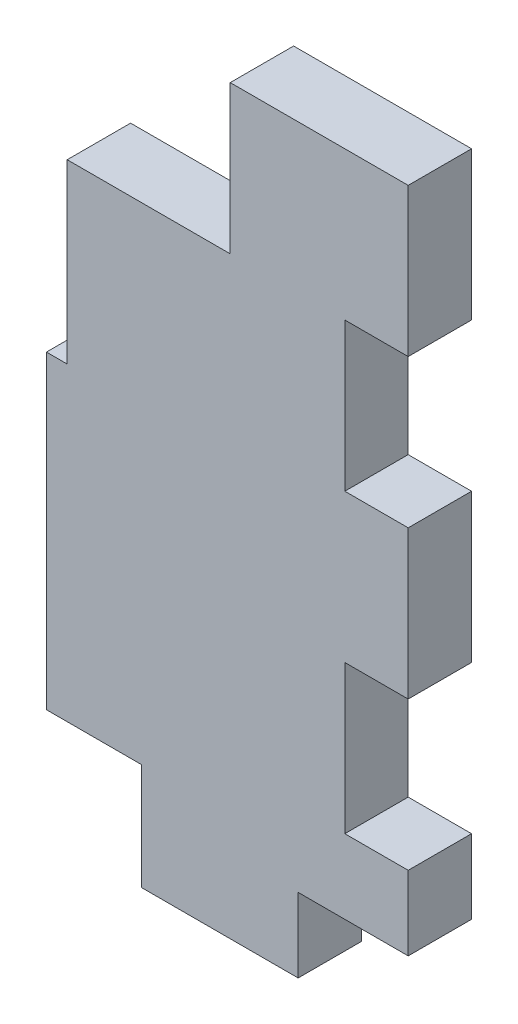
SolidWorks part; units mm, degrees
ref_plane "Front Plane" through (0, 0, 0) normal (0, 0, 1) x (1, 0, 0)
ref_plane "Top Plane" through (0, 0, 0) normal (0, 1, 0) x (1, 0, 0)
ref_plane "Right Plane" through (0, 0, 0) normal (1, 0, 0) x (0, 0, -1)
sketch "Sketch1" plane through (0, 0, 0) normal (0, 0, 1) x (1, 0, 0)
  line L0 (0, -0.475) -> (32.004, -0.475) construction
  line L4 (32.004, -26.67) -> (32.004, 26.67)
  line L5 (32.004, 26.67) -> (0, 26.67)
  line L6 (0, 26.67) -> (0, 12.9921)
  line L7 (0, 26.67) -> (0, -0.475) construction
  line L8 (8.2572, -26.67) -> (8.2572, -19.0119) construction
  line L9 (0, 26.67) -> (0, 12.9921) construction
  line L10 (32.004, 26.67) -> (27.4447, 26.67) construction
  line L11 (27.4447, 26.67) -> (27.4447, -26.67) construction
  line L12 (0, 12.9921) -> (27.4447, 12.9921) construction
  line L13 (0, 12.9921) -> (11.0096, 12.9921) construction
  line L19 (8.2572, -26.67) -> (32.004, -26.67) construction
  line L23 (8.2572, -19.0119) -> (12.8165, -19.0119) construction
  line L44 (32.004, 26.67) -> (27.4447, 26.67) construction
  line L45 (32.004, 26.67) -> (32.004, 16.002) construction
  line L46 (32.004, 16.002) -> (27.4447, 16.002) construction
  line L47 (27.4447, 26.67) -> (27.4447, 16.002) construction
  line L48 (27.4447, 16.002) -> (32.004, 16.002)
  line L49 (27.4447, 16.002) -> (27.4447, 5.334)
  line L50 (27.4447, 5.334) -> (32.004, 5.334)
  line L51 (32.004, 16.002) -> (32.004, 5.334)
  line L52 (27.4447, 5.334) -> (32.004, 5.334) construction
  line L53 (27.4447, 5.334) -> (27.4447, -5.334) construction
  line L54 (27.4447, -5.334) -> (32.004, -5.334) construction
  line L55 (32.004, 5.334) -> (32.004, -5.334) construction
  line L56 (27.4447, -5.334) -> (32.004, -5.334)
  line L57 (27.4447, -5.334) -> (27.4447, -16.002)
  line L58 (27.4447, -16.002) -> (32.004, -16.002)
  line L59 (32.004, -5.334) -> (32.004, -16.002)
  line L60 (27.4447, -16.002) -> (32.004, -16.002) construction
  line L61 (27.4447, -16.002) -> (27.4447, -26.67) construction
  line L62 (27.4447, -26.67) -> (32.004, -26.67) construction
  line L63 (32.004, -16.002) -> (32.004, -26.67) construction
  line L75 (6.4008, 21.336) -> (6.4008, 26.67) construction
  line L76 (6.4008, 21.336) -> (19.2024, 21.336) construction
  line L77 (6.4008, 21.336) -> (6.4008, 26.67) construction
  line L78 (6.4008, 26.67) -> (19.2024, 26.67)
  line L79 (19.2024, 21.336) -> (19.2024, 26.67)
  line L80 (19.2024, 21.336) -> (32.004, 21.336) construction
  line L81 (19.2024, 21.336) -> (19.2024, 26.67) construction
  line L82 (19.2024, 26.67) -> (32.004, 26.67) construction
  line L83 (32.004, 21.336) -> (32.004, 26.67) construction
  line L96 (12.8165, -19.0119) -> (12.8165, -26.67)
  line L97 (24.0884, -26.67) -> (24.0884, -21.336)
  line L98 (32.004, -21.336) -> (24.0884, -21.336)
  line L99 (0, 12.9921) -> (7.4752, 12.9921)
  line L100 (7.4752, 12.9921) -> (7.4752, 3.2715)
  line L101 (7.4752, 3.2715) -> (5.9802, 3.2715)
  line L103 (5.9802, -19.0119) -> (8.2572, -19.0119)
  line L104 (5.9802, -19.0119) -> (5.9802, 3.2715)
  line L105 (27.4447, 16.002) -> (0, 16.002) construction
  line L106 (19.2024, 21.336) -> (19.2024, 16.002)
  line L107 (19.2024, 16.002) -> (0, 16.002)
  line L108 (7.4752, 12.9921) -> (7.4752, 16.002)
  line L109 (7.4752, 16.002) -> (19.2024, 16.002)
  line L110 (12.8165, -19.0119) -> (8.2572, -19.0119)
  line L111 (12.8165, -26.67) -> (24.0884, -26.67)
  dimension "D2" = 53.34
  dimension "D6" = 4.5593
  dimension "D1" = 7.4752
  dimension "D3" = 9.7206
  dimension "D4" = 1.495
  dimension "D5" = 13.6779
  dimension "D7" = 4.5593
extrude "Boss-Extrude1" add sketch "Sketch1" along normal blind 4.5593
equation "\"D2@Sketch1\"=\"neck_height\""
equation "\"material_width\" = 0.1795"
equation "\"max32_width\" = 2.1"
equation "\"max32_length\" = 4.0"
equation "\"max32_hole_diameter\" = 0.12"
equation "\"max32_dist2hole_width\" = 0.1"
equation "\"max32_dist2hole1_length\" = 0.6"
equation "\"max32_dist2hole2_length\" = 3.8"
equation "\"head_height\" = 2.0"
equation "\"neck_height\" = \"max32_width\""
equation "\"washer_height\" = 0.1"
equation "\"wall_length\" = 3.5"
equation "\"wall_height\" = 1.5"
equation "\"extra_space\" = 0.25"
equation "\"arc_radius\" = \"wall_length\" + \"washer_height\" + \"neck_height\" + (\"head_height\"/2)"
equation "\"arc_wall_height\" = \"arc_radius\" + \"wall_length\" + \"extra_space\""
equation "\"foot_length\" = 1.0"
equation "\"peg_diameter\" = 0.2475"
equation "\"barring_diameter\" = 0.8657"
equation "\"imu_space\" = 0.8"
equation "\"encoder_height\" = 0.8587"
equation "\"encoder_sub_height\" = 0.3827"
equation "\"encoder_length\" = 1.1043"
equation "\"encoder_sub_length\" = 0.5886"
equation "\"encoder_width\" = 0.8669"
equation "\"D6@Sketch1\"=\"material_width\""
equation "\"D1@Boss-Extrude1\"=\"material_width\""
equation "\"D1@Sketch1\"=\"encoder_sub_length\"/2"
equation "\"D3@Sketch1\"=\"encoder_sub_height\""
equation "\"D4@Sketch1\"=\"encoder_sub_length\"/10"
equation "\"D5@Sketch1\"=\"material_width\"*3"
equation "\"D7@Sketch1\"=\"material_width\""
